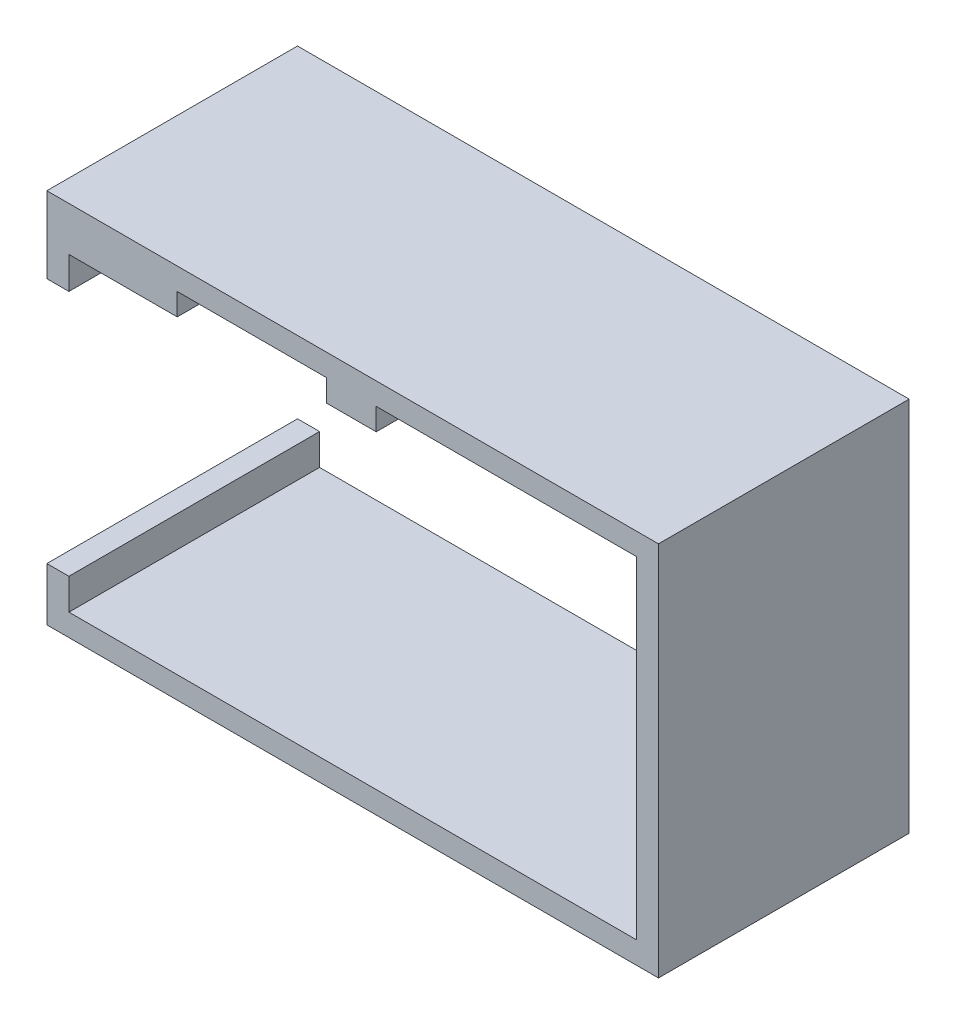
SolidWorks part; units mm, degrees
ref_plane "Front" through (0, 0, 0) normal (0, 0, 1) x (1, 0, 0)
ref_plane "Top" through (0, 0, 0) normal (0, 1, 0) x (1, 0, 0)
ref_plane "Right" through (0, 0, 0) normal (1, 0, 0) x (0, 0, -1)
sketch "Esquisse1" plane through (0, 0, 0) normal (0, 0, 1) x (1, 0, 0)
  line L0 (0, 0) -> (5660, 0)
  line L1 (5660, 0) -> (5660, 3310)
  line L2 (5660, 3310) -> (3065, 3310)
  line L3 (3065, 3310) -> (3065, 3090)
  line L4 (3065, 3090) -> (2570, 3090)
  line L5 (2570, 3090) -> (2570, 3310)
  line L6 (2570, 3310) -> (1080, 3310)
  line L7 (1080, 3310) -> (1080, 3090)
  line L8 (1080, 3090) -> (0, 3090)
  line L9 (0, 3090) -> (0, 2770)
  line L10 (0, 2770) -> (-220, 2770)
  line L11 (-220, 2770) -> (-220, 3530)
  line L12 (-220, 3530) -> (5880, 3530)
  line L13 (5880, 3530) -> (5880, -220)
  line L14 (5880, -220) -> (-220, -220)
  line L15 (-220, -220) -> (-220, 310)
  line L16 (-220, 310) -> (0, 310)
  line L17 (0, 310) -> (0, 0)
  point P13 (1681.7318, 3310)
  point P20 (517.6296, 3090)
  point P21 (1205.6478, 3090)
  point P22 (0, 2770)
  point P23 (-1206.1676, 2770)
  point P24 (0, 2770)
  point P25 (-968.9763, 2770)
  point P26 (-1975.1754, 2770)
  point P27 (-68.7113, 2770)
  dimension "D1" = 220
  dimension "D2" = 220
  dimension "D3" = 310
  dimension "D4" = 3310
  dimension "D5" = 220
  dimension "D6" = 220
  dimension "D7" = 320
  dimension "D8" = 220
  dimension "D9" = 2595
  dimension "D10" = 495
  dimension "D11" = 1490
  dimension "D12" = 1080
  dimension "D13" = 220
extrude "Boss.-Extru.1" add sketch "Esquisse1" along normal blind 2500
